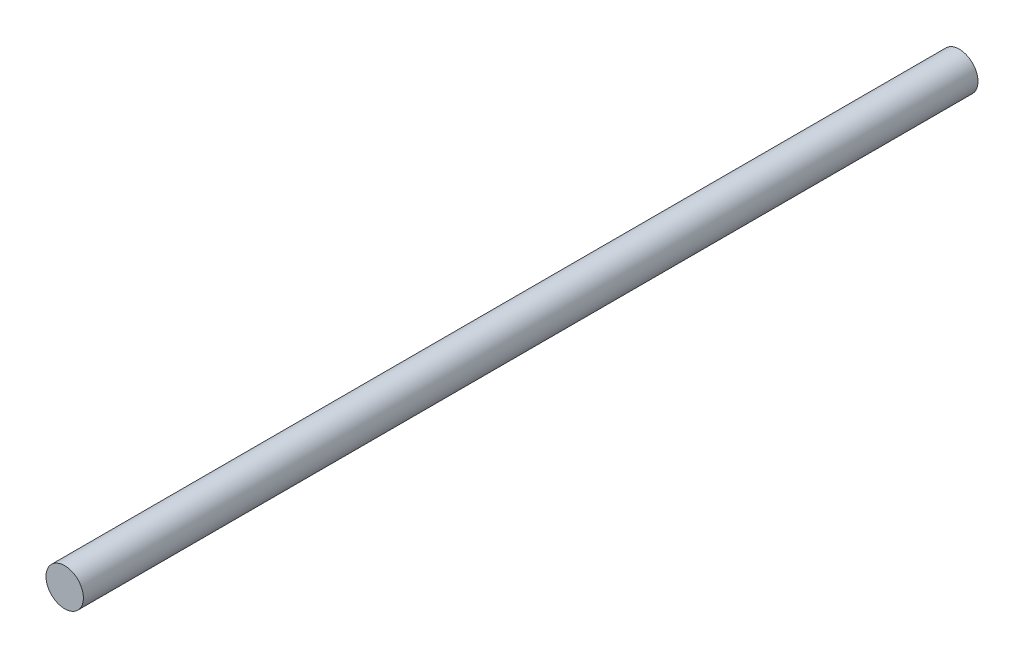
SolidWorks part; units mm, degrees
ref_plane "Front Plane" through (0, 0, 0) normal (0, 0, 1) x (1, 0, 0)
ref_plane "Top Plane" through (0, 0, 0) normal (0, 1, 0) x (1, 0, 0)
ref_plane "Right Plane" through (0, 0, 0) normal (1, 0, 0) x (0, 0, -1)
sketch "Sketch1" plane through (0, 0, 0) normal (0, 0, 1) x (1, 0, 0)
  circle A0 centre (0, 0) radius 6.35
  dimension "D1" = 12.7
extrude "Boss-Extrude1" add sketch "Sketch1" against normal blind 303.53
